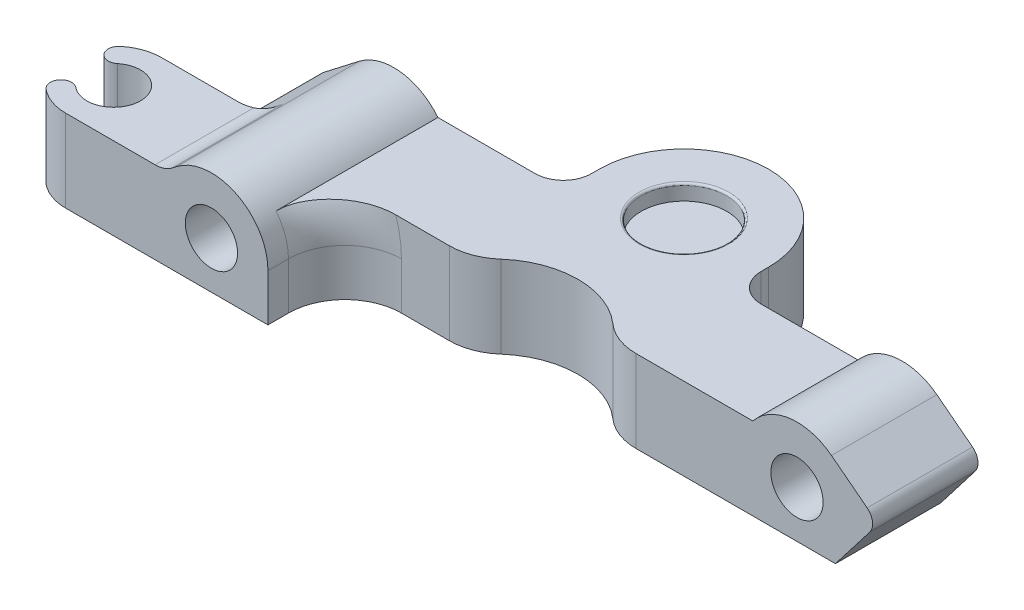
SolidWorks part; units mm, degrees
ref_plane "Front Plane" through (0, 0, 0) normal (0, 0, 1) x (1, 0, 0)
ref_plane "Top Plane" through (0, 0, 0) normal (0, 1, 0) x (1, 0, 0)
ref_plane "Right Plane" through (0, 0, 0) normal (1, 0, 0) x (0, 0, -1)
sketch "Sketch1" plane through (0, 0, 0) normal (0, 1, 0) x (1, 0, 0)
  line L0 (10.0004, -2.54) -> (-10.0004, -2.54) construction
  line L1 (10.0004, -2.54) -> (-10.0004, -2.54)
  line L2 (-20.7235, -2.54) -> (-20.7235, -7.65) construction
  line L3 (20.7235, -2.54) -> (20.7235, -18.7) construction
  line L4 (-20.7235, -2.54) -> (-20.7235, -7.65)
  line L5 (20.7235, -2.54) -> (20.7235, -18.7)
  line L6 (3.5, -17) -> (-3.5, -17) construction
  line L7 (-3.5, -17) -> (-3.5, -10) construction
  line L8 (3.5, -17) -> (3.5, -10) construction
  line L9 (3.5, -10) -> (-3.5, -10) construction
  line L10 (3.5, -17) -> (-3.5, -17)
  line L11 (-3.5, -17) -> (-3.5, -10)
  line L12 (3.5, -17) -> (3.5, -10)
  line L13 (3.5, -10) -> (-3.5, -10)
  line L14 (10.0004, 0) -> (-10.0004, 0) construction
  line L15 (10.0004, 0) -> (-10.0004, 0)
  circle A0 centre (0, 0) radius 3 construction
  circle A1 centre (0, 0) radius 3
  circle A3 centre (0, -13.5) radius 1.8
  circle A4 centre (0, -13.5) radius 1.8
  dimension "D1" = 0
ref_plane "Plane1" through (0, 0, 2.54) normal (0, 0, 1) x (1, 0, 0)
sketch "Sketch2" plane through (0, 0, 2.54) normal (0, 0, 1) x (1, 0, 0)
  line L0 (-10.8, -5.4256) -> (-14.8017, -0.0978) construction
  line L1 (14.8017, -0.0978) -> (10.8, -5.4256) construction
  line L2 (-10.8, -5.4256) -> (-14.8017, -0.0978)
  line L3 (14.8017, -0.0978) -> (10.8, -5.4256)
  circle A0 centre (-18, -2.5) radius 2 construction
  circle A1 centre (18, -2.5) radius 2 construction
  circle A2 centre (-18, -2.5) radius 2
  circle A3 centre (18, -2.5) radius 2
  arc A4 (-14.8017, -0.0978) -> (-20.4428, 0.6675) centre (-18, -2.5) ccw construction
  arc A5 (20.4428, 0.6675) -> (14.8017, -0.0978) centre (18, -2.5) ccw construction
  arc A6 (-14.8017, -0.0978) -> (-20.4428, 0.6675) centre (-18, -2.5) ccw
  arc A7 (20.4428, 0.6675) -> (14.8017, -0.0978) centre (18, -2.5) ccw
ref_plane "Plane2" through (0, -5.825, 0) normal (0, 1, 0) x (1, 0, 0)
sketch "Sketch3" plane through (0, 0, 0) normal (0, 1, 0) x (1, 0, 0)
  line L0 (20.7235, -2.54) -> (20.7235, -18.7) construction
  line L1 (-20.7235, -10) -> (20.7235, -10)
  line L2 (-20.7235, -10) -> (-20.7235, -2.54)
  line L3 (-20.7235, -2.54) -> (20.7235, -2.54)
  line L4 (20.7235, -10) -> (20.7235, -2.54)
  line L5 (-20.7235, -2.54) -> (-20.7235, -7.65) construction
  line L6 (10.0004, -2.54) -> (-10.0004, -2.54) construction
  line L7 (3.5, -10) -> (-3.5, -10) construction
extrude "Boss-Extrude1" add sketch "Sketch3" against normal up to surface (5.825 mm away) up to plane "Plane2"
sketch "Sketch4" plane through (0, 0, 2.54) normal (0, 0, 1) x (1, 0, 0)
  line L0 (20.7235, 0) -> (-20.7235, 0) construction
  line L1 (20.7235, 0) -> (14.8775, 0)
  line L3 (0, 4.1152) -> (0, -4.1152) construction
  line L8 (10.0004, 0) -> (-10.0004, 0) construction
  line L12 (21.0393, -5.825) -> (22.1244, -4.4179) construction
  line L13 (21.0393, -5.825) -> (22.1244, -4.4179) construction
  line L14 (26.3321, -3.8744) -> (20.4428, 0.6675) construction
  line L15 (23.7585, -1.8896) -> (20.4428, 0.6675)
  line L16 (20.7235, -5.825) -> (23.7585, -1.8896)
  line L17 (20.7235, 0) -> (20.7235, -5.825)
  line L23 (-20.7235, 0) -> (-20.7235, -5.825)
  line L24 (-20.7235, -5.825) -> (-23.7585, -1.8896)
  line L25 (-23.7585, -1.8896) -> (-20.4428, 0.6675)
  line L26 (-20.7235, 0) -> (-14.8775, 0)
  arc A2 (20.4428, 0.6675) -> (14.8017, -0.0978) centre (18, -2.5) ccw construction
  arc A3 (20.4428, 0.6675) -> (14.8775, 0) centre (18, -2.5) ccw
  arc A6 (-20.4428, 0.6675) -> (-14.8775, 0) centre (-18, -2.5) cw
  point P12 (0, 0)
  point P13 (0, 0)
extrude "Boss-Extrude3" add sketch "Sketch4" along normal up to surface (7.46 mm away) up to face at (0, -2.9125, 10)
sketch "Sketch6" plane through (0, 0, 0) normal (0, 1, 0) x (1, 0, 0)
  line L0 (6, 0) -> (6, -2.54)
  line L1 (10.0004, -2.54) -> (-10.0004, -2.54) construction
  line L2 (-6, 0) -> (-6, -2.54)
  line L3 (-6, -2.54) -> (6, -2.54)
  arc A0 (6, 0) -> (-6, 0) centre (0, 0) ccw
  circle A1 centre (0, 0) radius 3 construction
  point P5 (6, 0)
  point P6 (-6, 0)
  dimension "D1" = 3
extrude "Boss-Extrude4" add sketch "Sketch6" against normal up to surface (5.825 mm away) up to face at (0, -5.825, 6.27)
sketch "Sketch7" plane through (0, 0, 0) normal (0, 1, 0) x (1, 0, 0)
  line L0 (10.0004, 0) -> (-10.0004, 0) construction
  line L1 (20.7235, -2.54) -> (20.7235, -18.7) construction
  line L2 (-20.7235, -2.54) -> (-20.7235, -7.65) construction
  line L3 (10.0004, -2.54) -> (-10.0004, -2.54) construction
  line L4 (3.5, -10) -> (-3.5, -10)
  line L5 (-3.5, -10) -> (-3.5, -17)
  line L6 (-3.5, -17) -> (3.5, -17)
  line L7 (3.5, -17) -> (3.5, -10)
  line L8 (3.5, -10) -> (-3.5, -10) construction
  line L9 (-3.5, -10) -> (-3.5, -17) construction
  line L10 (-3.5, -17) -> (3.5, -17) construction
  line L11 (3.5, -17) -> (3.5, -10) construction
  line L12 (10.0004, 0) -> (-10.0004, 0) construction
  line L13 (20.7235, -2.54) -> (20.7235, -18.7) construction
  line L14 (-20.7235, -2.54) -> (-20.7235, -7.65) construction
  line L15 (10.0004, -2.54) -> (-10.0004, -2.54) construction
  circle A1 centre (0, -13.5) radius 1.8
  circle A2 centre (0, -13.5) radius 1.8 construction
  circle A3 centre (0, 0) radius 3.03
  circle A4 centre (0, 0) radius 3
  circle A5 centre (0, 0) radius 3 construction
  dimension "D4" = 0.03
  dimension "D1" = 0
  dimension "D2" = 0
  dimension "D3" = 0
extrude "Cut-Extrude1" cut sketch "Sketch7" against normal blind 1.1
fillet "Fillet1" radius 0.15 1 edges at (0, 0, 3.03)
sketch "Sketch8" plane through (0, 0, 2.54) normal (0, 0, -1) x (-1, 0, 0)
  circle A0 centre (-18, -2.5) radius 1.85
  circle A1 centre (18, -2.5) radius 1.85
  dimension "D1" = 3.7
extrude "Cut-Extrude2" cut sketch "Sketch8" against normal through all
fillet "Fillet2" radius 1 2 edges at (23.7585, -1.8896, 6.27) (-23.7585, -1.8896, 6.27)
fillet "Fillet3" radius 2 2 edges at (-6, -2.9125, 2.54) (6, -2.9125, 2.54)
sketch "Sketch9" plane through (0, 0, 0) normal (0, 1, 0) x (1, 0, 0)
  line L3 (-20.7235, -8.65) -> (-28.3223, -8.65)
  line L4 (-20.7235, -15.45) -> (-20.7235, -8.65)
  line L5 (-28.3223, -15.45) -> (-20.7235, -15.45)
  line L6 (-20.7235, -8.65) -> (-28.3223, -8.65)
  line L7 (-20.7235, -15.45) -> (-20.7235, -8.65)
  line L8 (-28.3223, -15.45) -> (-20.7235, -15.45)
  arc A5 (-30.4769, -14.6802) -> (-28.3223, -15.45) centre (-28.3223, -12.05) ccw
  arc A6 (-29.5263, -13.5198) -> (-30.4769, -14.6802) centre (-30.0016, -14.1) ccw
  arc A7 (-29.5263, -13.5198) -> (-29.5263, -10.5802) centre (-28.3223, -12.05) ccw
  arc A8 (-30.4769, -9.4198) -> (-29.5263, -10.5802) centre (-30.0016, -10) ccw
  arc A9 (-28.3223, -8.65) -> (-30.4769, -9.4198) centre (-28.3223, -12.05) ccw
  arc A10 (-30.4769, -14.6802) -> (-28.3223, -15.45) centre (-28.3223, -12.05) ccw
  arc A11 (-29.5263, -13.5198) -> (-30.4769, -14.6802) centre (-30.0016, -14.1) ccw
  arc A12 (-29.5263, -13.5198) -> (-29.5263, -10.5802) centre (-28.3223, -12.05) ccw
  arc A13 (-30.4769, -9.4198) -> (-29.5263, -10.5802) centre (-30.0016, -10) ccw
  arc A14 (-28.3223, -8.65) -> (-30.4769, -9.4198) centre (-28.3223, -12.05) ccw
  point P6 (0, 0)
  dimension "D1" = 0
sketch "Sketch10" plane through (0, 0, 10) normal (0, 0, 1) x (1, 0, 0)
  line L0 (-14, -2.5) -> (-14, -5.825)
  line L6 (-20.4428, 0.6675) -> (-22.9666, -1.279)
  line L7 (-23.1478, -2.6815) -> (-20.7235, -5.825)
  line L8 (-20.7235, -5.825) -> (20.7235, -5.825)
  line L9 (20.7235, -5.825) -> (23.1478, -2.6815)
  line L10 (22.9666, -1.279) -> (20.4428, 0.6675)
  line L11 (14.8775, 0) -> (-14.8775, 0)
  line L12 (-20.4428, 0.6675) -> (-22.9666, -1.279)
  line L13 (-23.1478, -2.6815) -> (-20.7235, -5.825)
  line L14 (-20.7235, -5.825) -> (-14, -5.825)
  circle A1 centre (-18, -2.5) radius 1.85
  circle A2 centre (-18, -2.5) radius 1.85
  arc A4 (-22.9666, -1.279) -> (-23.1478, -2.6815) centre (-22.3559, -2.0708) ccw
  arc A5 (23.1478, -2.6815) -> (22.9666, -1.279) centre (22.3559, -2.0708) ccw
  arc A6 (20.4428, 0.6675) -> (14.8775, 0) centre (18, -2.5) ccw
  arc A7 (-14.8775, 0) -> (-20.4428, 0.6675) centre (-18, -2.5) ccw
  arc A8 (-22.9666, -1.279) -> (-23.1478, -2.6815) centre (-22.3559, -2.0708) ccw
  arc A11 (-14, -2.5) -> (-20.4428, 0.6675) centre (-18, -2.5) ccw
  dimension "D1" = 0
  dimension "D2" = 0
extrude "Boss-Extrude5" add sketch "Sketch10" along normal up to vertex (5.45 mm away) up to point (-20.7235, 0, 15.45)
extrude "Boss-Extrude6" add sketch "Sketch9" against normal up to surface (5.825 mm away) up to face at (-2.3333, -5.825, 4.7474)
sketch "Sketch11" plane through (0, 0, 0) normal (0, 1, 0) x (1, 0, 0)
  circle A0 centre (0, -13.5) radius 6
  dimension "D1" = 12
extrude "Cut-Extrude3" cut sketch "Sketch11" against normal through all
fillet "Fillet4" radius 1 3 edges at (-22.1375, -0.6395, 8.65) (-23.3477, -1.9427, 8.65) (-21.9357, -4.2533, 8.65)
fillet "Fillet5" radius 2 1 edges at (-21.3083, 0, 11.55)
fillet "Fillet6" radius 4 4 edges at (-14.2257, -1.1752, 10) (-14, -4.1625, 10) (4.8734, -2.9125, 10) (-4.8734, -2.9125, 10)
